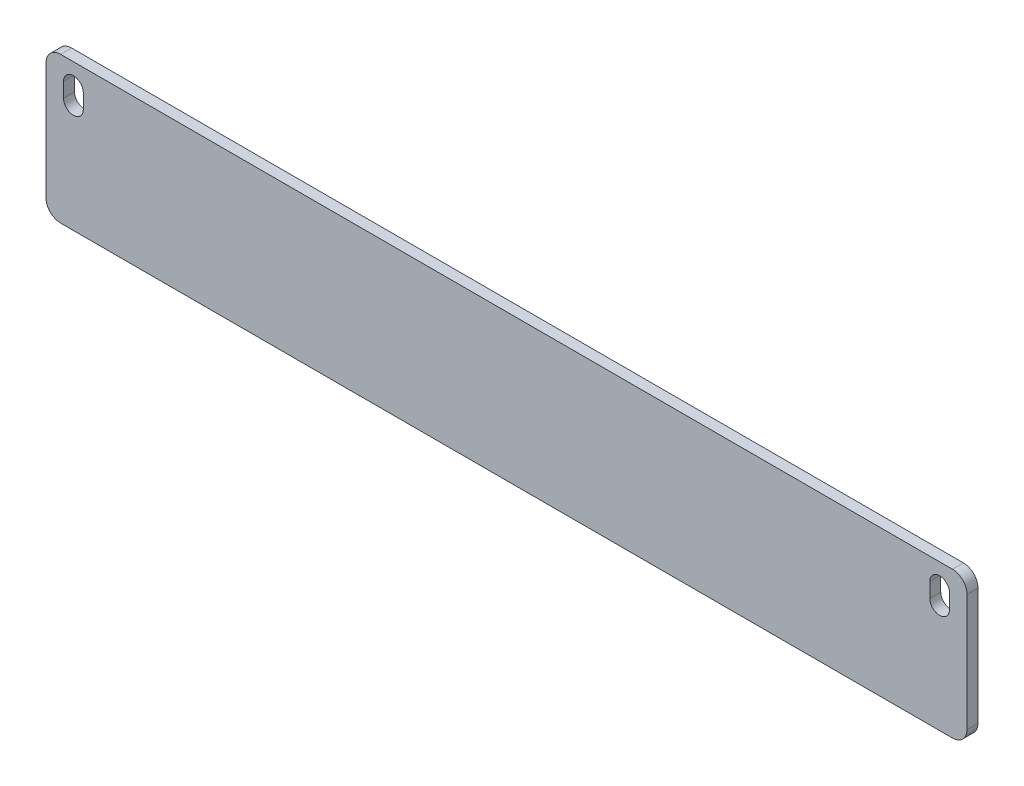
SolidWorks part; units mm, degrees
ref_plane "Front Plane" through (0, 0, 0) normal (0, 0, 1) x (1, 0, 0)
ref_plane "Top Plane" through (0, 0, 0) normal (0, 1, 0) x (1, 0, 0)
ref_plane "Right Plane" through (0, 0, 0) normal (1, 0, 0) x (0, 0, -1)
sketch "Sketch1" plane through (0, 0, 0) normal (0, 0, 1) x (1, 0, 0)
  line L0 (7.5, 34) -> (7.5, 30) construction
  line L7 (0, 0) -> (252, 0)
  line L10 (0, 0) -> (0, 40)
  line L11 (0, 40) -> (252, 40)
  line L12 (252, 0) -> (252, 40)
  line L13 (10.2, 34) -> (10.2, 30)
  line L14 (4.8, 34) -> (4.8, 30)
  line L15 (244.5, 34) -> (244.5, 30) construction
  line L16 (247.2, 34) -> (247.2, 30)
  line L17 (241.8, 34) -> (241.8, 30)
  arc A4 (10.2, 34) -> (4.8, 34) centre (7.5, 34) ccw
  arc A5 (4.8, 30) -> (10.2, 30) centre (7.5, 30) ccw
  arc A6 (247.2, 34) -> (241.8, 34) centre (244.5, 34) ccw
  arc A7 (241.8, 30) -> (247.2, 30) centre (244.5, 30) ccw
  point P7 (7.5, 32)
  point P12 (244.5, 32)
  dimension "D3" = 2.7
  dimension "D1" = 40
  dimension "D2" = 252
  dimension "D4" = 7.5
  dimension "D5" = 7.5
  dimension "D6" = 4
  dimension "D7" = 6
  dimension "D8" = 4
  dimension "D9" = 6
extrude "Boss-Extrude1" add sketch "Sketch1" along normal blind 3
fillet "Fillet1" radius 4 4 edges at (252, 0, 1.5) (252, 40, 1.5) (0, 0, 1.5) (0, 40, 1.5)
